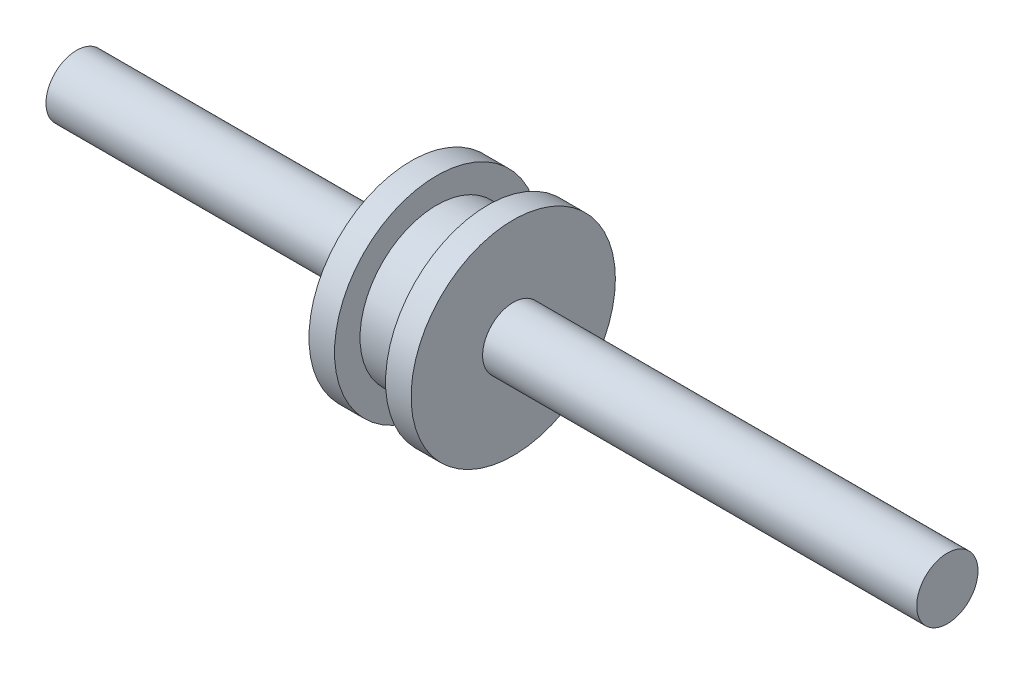
SolidWorks part; units mm, degrees
ref_plane "Front Plane" through (0, 0, 0) normal (0, 0, 1) x (1, 0, 0)
ref_plane "Top Plane" through (0, 0, 0) normal (0, 1, 0) x (1, 0, 0)
ref_plane "Right Plane" through (0, 0, 0) normal (1, 0, 0) x (0, 0, -1)
sketch "Sketch1" plane through (0, 0, 0) normal (1, 0, 0) x (0, 0, -1)
  circle A0 centre (0, 0) radius 6
  dimension "D1" = 12
extrude "Boss-Extrude1" add sketch "Sketch1" along normal blind 65.5
sketch "Sketch2" plane through (65.5, 0, 0) normal (1, 0, 0) x (0, 0, -1)
  circle A0 centre (0, 0) radius 20
  dimension "D1" = 40
extrude "Boss-Extrude2" add sketch "Sketch2" along normal blind 5
sketch "Sketch3" plane through (70.5, 0, 0) normal (1, 0, 0) x (0, 0, -1)
  circle A0 centre (0, 0) radius 15
  dimension "D1" = 30
extrude "Boss-Extrude3" add sketch "Sketch3" along normal blind 10
sketch "Sketch4" plane through (80.5, 0, 0) normal (1, 0, 0) x (0, 0, -1)
  circle A0 centre (0, 0) radius 20
extrude "Boss-Extrude4" add sketch "Sketch4" along normal blind 5
sketch "Sketch5" plane through (85.5, 0, 0) normal (1, 0, 0) x (0, 0, -1)
  circle A0 centre (0, 0) radius 6
  dimension "D1" = 12
extrude "Boss-Extrude5" add sketch "Sketch5" along normal blind 85
